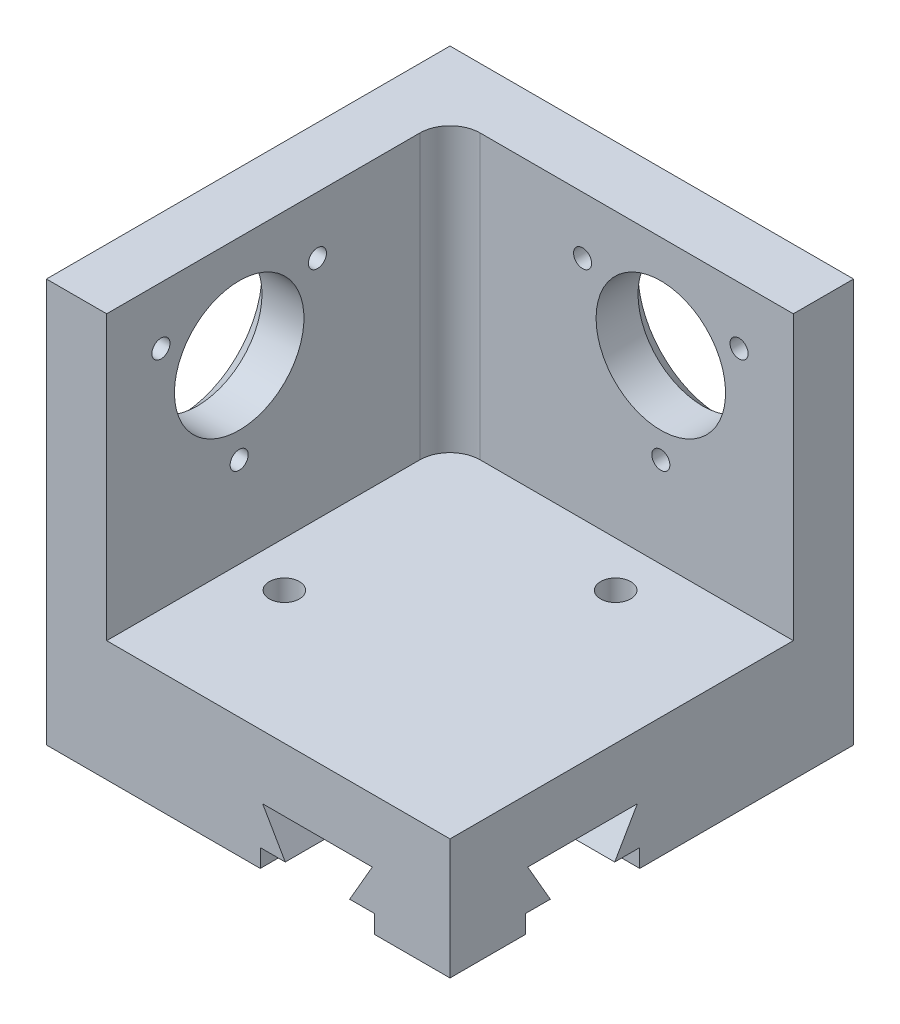
SolidWorks part; units mm, degrees
material "Alumina"
ref_plane "Front Plane" through (0, 0, 0) normal (0, 0, 1) x (1, 0, 0)
ref_plane "Top Plane" through (0, 0, 0) normal (0, 1, 0) x (1, 0, 0)
ref_plane "Right Plane" through (0, 0, 0) normal (1, 0, 0) x (0, 0, -1)
sketch "Sketch1" plane through (0, 0, 0) normal (0, 1, 0) x (1, 0, 0)
  line L1 (33.5, -33.5) -> (-33.5, -33.5)
  line L2 (33.5, -33.5) -> (33.5, 33.5)
  line L3 (33.5, 33.5) -> (-33.5, 33.5)
  line L4 (-33.5, -33.5) -> (-33.5, 33.5)
  line L5 (33.5, -33.5) -> (-33.5, 33.5) construction
  line L6 (33.5, 33.5) -> (-33.5, -33.5) construction
  point P0 (0, 0)
  dimension "D1" = 67
  dimension "D2" = 67
extrude "Boss-Extrude1" add sketch "Sketch1" along normal blind 67
sketch "Sketch2" plane through (0, 67, 0) normal (0, 1, 0) x (1, 0, 0)
  line L0 (-23.5, -33.5) -> (-23.5, 23.5)
  line L1 (-33.5, -33.5) -> (33.5, -33.5) construction
  line L2 (-23.5, 23.5) -> (33.5, 23.5)
  line L3 (33.5, -33.5) -> (33.5, 33.5) construction
  line L4 (33.5, 23.5) -> (33.5, -33.5)
  line L5 (33.5, -33.5) -> (-23.5, -33.5)
  line L6 (-33.5, 33.5) -> (-33.5, -33.5) construction
  line L7 (33.5, 33.5) -> (-33.5, 33.5) construction
  dimension "D1" = 10
  dimension "D2" = 10
extrude "Cut-Extrude1" cut sketch "Sketch2" against normal blind 47
sketch "Sketch3" plane through (-33.5, 0, 0) normal (-1, 0, 0) x (0, 0, 1)
  line L3 (-33.5, 0) -> (33.5, 0) construction
  line L4 (33.5, 67) -> (33.5, 0) construction
  circle A0 centre (11.5, 50) radius 10.75
  dimension "D1" = 21.5
  dimension "D2" = 22
  dimension "D3" = 50
extrude "Cut-Extrude2" cut sketch "Sketch3" against normal up to next
sketch "Sketch4" plane through (0, 0, -33.5) normal (0, 0, -1) x (-1, 0, 0)
  line L3 (-33.5, 67) -> (-33.5, 0) construction
  line L4 (-33.5, 0) -> (33.5, 0) construction
  circle A0 centre (-11.5, 50) radius 10.75
  dimension "D1" = 21.5
  dimension "D2" = 22
  dimension "D3" = 50
extrude "Cut-Extrude3" cut sketch "Sketch4" against normal up to next
hole_wizard "Ø5.0 (5) Diameter Hole1" positions "Sketch6" profile "Sketch5" hole size "Ø5.0" standard "DIN"
sketch "Sketch6" plane through (0, 20, 0) normal (0, 1, 0) x (-1, 0, 0)
  line L0 (-33.5, 33.5) -> (-33.5, -23.5) construction
  line L3 (-33.5, -23.5) -> (23.5, -23.5) construction
  line L4 (23.5, -23.5) -> (23.5, 33.5) construction
  line L5 (23.5, 33.5) -> (-33.5, 33.5) construction
  point P0 (16, 11.5)
  point P1 (-11.5, -16)
  dimension "D1" = 22
  dimension "D2" = 7.5
  dimension "D3" = 7.5
  dimension "D4" = 22
sketch "Sketch5" plane through (-16, 20, 11.5) normal (1, 0, 0) x (0, 0, 1)
  line L0 (0, 0) -> (0, 6.5022)
  line L1 (0, 6.5022) -> (2.5, 5)
  line L2 (2.5, 5) -> (2.5, 0)
  line L5 (2.5, 0) -> (0, 0)
  line L10 (0, 6.5022) -> (-2.5, 5) construction
  line L11 (0, -6.35) -> (0, 107.95) construction
  dimension "Hole Dia." = 5
  dimension "Hole Depth" = 5
  dimension "Drill Angle" = 118
fillet "Fillet1" radius 5 1 edges at (-23.5, 43.5, -23.5)
chamfer "Chamfer1" distance 3.04 angle 45 2 edges at (-33.5, 50, 22.25) (0.75, 50, -33.5)
sketch "Sketch7" plane through (33.5, 0, 0) normal (1, 0, 0) x (0, 0, -1)
  line L0 (-11.5, -1.6232) -> (-11.5, 13.3768) construction
  line L1 (-2.4, 9.5) -> (-20.6, 9.5)
  line L2 (-20.6, 9.5) -> (-16.8472, 3)
  line L3 (-33.5, 0) -> (33.5, 0) construction
  line L4 (-21, 0) -> (-2, 0)
  line L6 (-16.8472, 3) -> (-21, 3)
  line L7 (-21, 3) -> (-21, 0)
  line L8 (-2, 3) -> (-2, 0)
  line L9 (-6.1528, 3) -> (-2, 3)
  line L10 (-2.4, 9.5) -> (-6.1528, 3)
  point P11 (-11.5, 9.5)
  point P17 (-11.5, 9.5)
  dimension "D1" = 9.1
  dimension "D2" = 9.5
  dimension "D3" = 60
  dimension "D4" = 3
  dimension "D5" = 15
  dimension "D6" = 9.5
extrude "Cut-Extrude4" cut sketch "Sketch7" against normal up to next
sketch "Sketch8" plane through (0, 0, 33.5) normal (0, 0, 1) x (1, 0, 0)
  line L0 (11.5, -1.704) -> (11.5, 20.704) construction
  line L1 (2.4, 9.5) -> (20.6, 9.5)
  line L2 (-33.5, 9.5) -> (33.5, 9.5) construction
  line L3 (2.4, 9.5) -> (6.1528, 3)
  line L4 (-33.5, 0) -> (33.5, 0) construction
  line L5 (2, 0) -> (21, 0)
  line L6 (21, 3) -> (21, 0)
  line L7 (6.1528, 3) -> (2, 3)
  line L8 (-33.5, 3) -> (33.5, 3) construction
  line L9 (2, 3) -> (2, 0)
  line L10 (16.8472, 3) -> (21, 3)
  line L11 (20.6, 9.5) -> (16.8472, 3)
  point P13 (11.5, 0)
  point P14 (11.5, 9.5)
  point P18 (11.5, 0)
  point P22 (11.5, 9.5)
  dimension "D1" = 9.1
  dimension "D2" = 60
  dimension "D3" = 9.5
extrude "Cut-Extrude5" cut sketch "Sketch8" against normal through all
sketch "Sketch9" plane through (-33.5, 0, 0) normal (-1, 0, 0) x (0, 0, 1)
  circle A0 centre (-1.4904, 57.5) radius 1.5
  circle A1 centre (24.4904, 57.5) radius 1.5
  circle A2 centre (11.5, 35) radius 1.5
  dimension "D1" = 3
  dimension "D2" = 3
  dimension "D3" = 3
extrude "Cut-Extrude6" cut sketch "Sketch9" against normal blind 10
sketch "Sketch10" plane through (0, 0, -33.5) normal (0, 0, -1) x (-1, 0, 0)
  circle A0 centre (1.4904, 57.5) radius 1.5
  circle A1 centre (-24.4904, 57.5) radius 1.5
  circle A2 centre (-11.5, 35) radius 1.5
  dimension "D1" = 3
  dimension "D2" = 3
  dimension "D3" = 3
extrude "Cut-Extrude7" cut sketch "Sketch10" against normal blind 10
